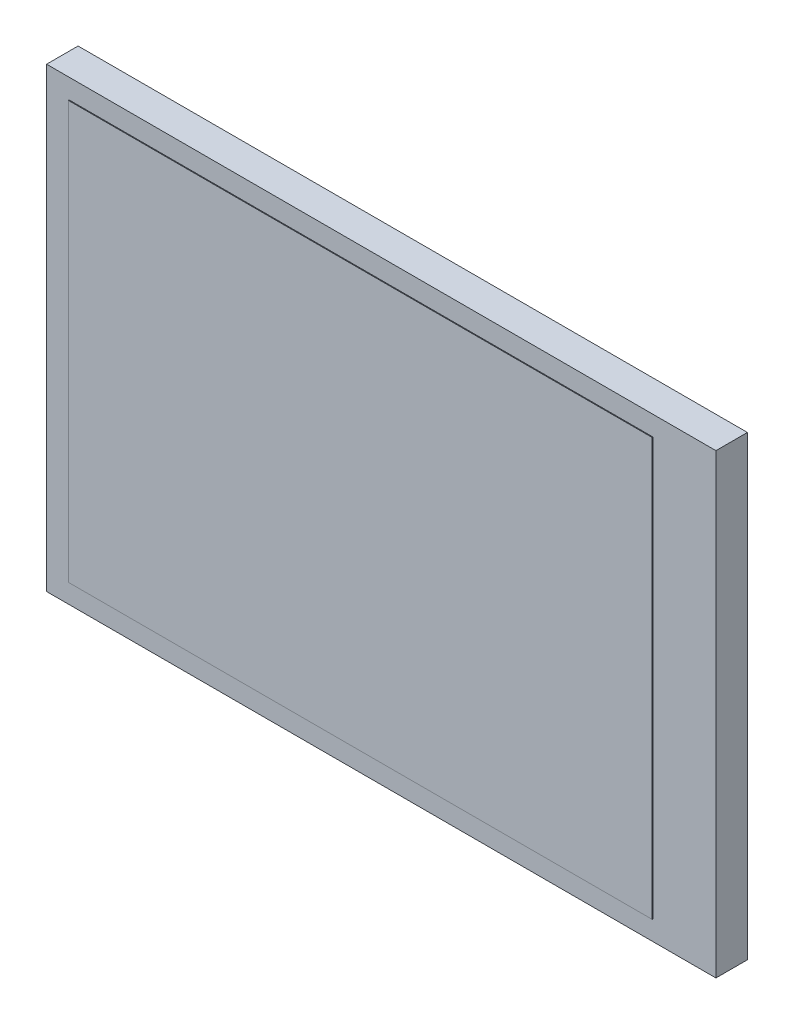
SolidWorks part; units mm, degrees
ref_plane "Front Plane" through (0, 0, 0) normal (0, 0, 1) x (1, 0, 0)
ref_plane "Top Plane" through (0, 0, 0) normal (0, 1, 0) x (1, 0, 0)
ref_plane "Right Plane" through (0, 0, 0) normal (1, 0, 0) x (0, 0, -1)
sketch "Sketch1" plane through (0, 0, 0) normal (0, 0, 1) x (1, 0, 0)
  line L1 (0, 0) -> (-85, 0)
  line L2 (0, 0) -> (0, 58)
  line L3 (0, 58) -> (-85, 58)
  line L4 (-85, 0) -> (-85, 58)
  dimension "D1" = 85
  dimension "D2" = 58
extrude "Boss-Extrude1" add sketch "Sketch1" along normal blind 4
sketch "Sketch2" plane through (0, 0, 4) normal (0, 0, 1) x (1, 0, 0)
  line L0 (-82.1441, 55.5) -> (-82.1441, 2.5)
  line L1 (-82.1441, 2.5) -> (-8, 2.5)
  line L2 (-8, 2.5) -> (-8, 55.5)
  line L3 (-8, 55.5) -> (-82.1441, 55.5)
  dimension "D1" = 2.5
  dimension "D2" = 2.5
  dimension "D3" = 8
extrude "Boss-Extrude2" add sketch "Sketch2" along normal blind 0.1
